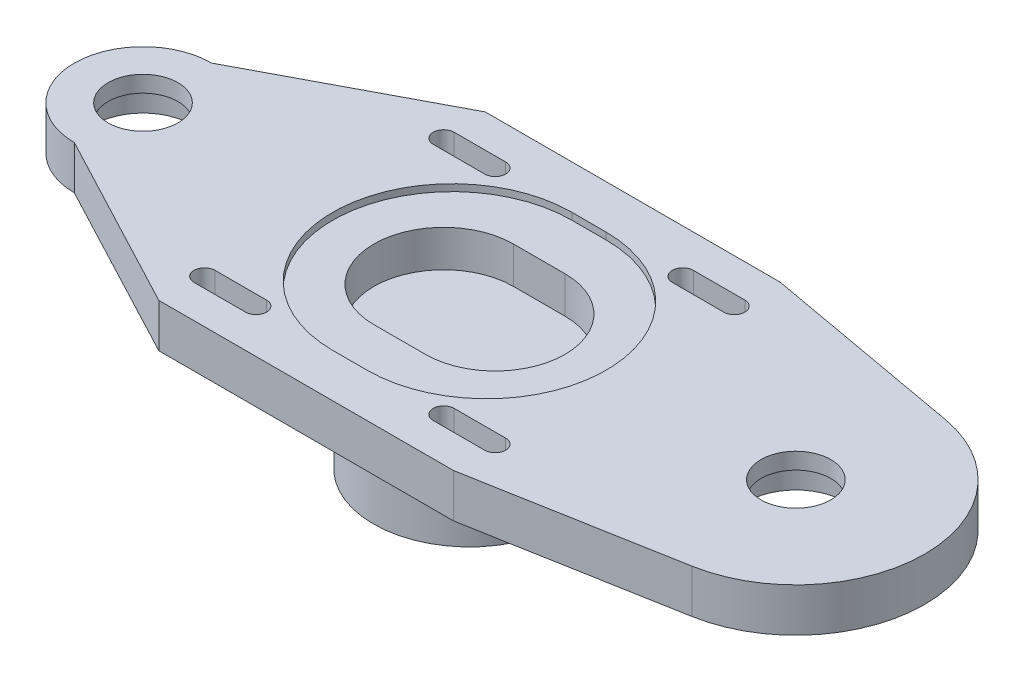
SolidWorks part; units mm, degrees
ref_plane "Front Plane" through (0, 0, 0) normal (0, 0, 1) x (1, 0, 0)
ref_plane "Top Plane" through (0, 0, 0) normal (0, 1, 0) x (1, 0, 0)
ref_plane "Right Plane" through (0, 0, 0) normal (1, 0, 0) x (0, 0, -1)
sketch "Sketch1" plane through (0, 0, 0) normal (0, 1, 0) x (1, 0, 0)
  line L0 (-95, 0) -> (0, 0) construction
  line L1 (-34.8, 34.8) -> (34.8, 34.8) construction
  line L2 (-34.8, 34.8) -> (-34.8, -34.8) construction
  line L3 (-34.8, -34.8) -> (34.8, -34.8) construction
  line L4 (34.8, 34.8) -> (34.8, -34.8) construction
  line L5 (-34.8, 34.8) -> (34.8, -34.8) construction
  line L6 (-34.8, -34.8) -> (34.8, 34.8) construction
  line L7 (-42.9, 47.5) -> (42.9, 47.5)
  line L8 (-42.9, 47.5) -> (-42.9, -47.5) construction
  line L9 (-42.9, -47.5) -> (42.9, -47.5)
  line L10 (42.9, 47.5) -> (42.9, -47.5) construction
  line L11 (-42.9, 47.5) -> (42.9, -47.5) construction
  line L12 (-42.9, -47.5) -> (42.9, 47.5) construction
  line L13 (0, 0) -> (95, 0) construction
  line L14 (-42.3, 34.8) -> (-27.3, 34.8) construction
  line L15 (-42.3, 37.85) -> (-27.3, 37.85)
  line L16 (-42.3, 31.75) -> (-27.3, 31.75)
  line L17 (42.3, 34.8) -> (27.3, 34.8) construction
  line L18 (42.3, 31.75) -> (27.3, 31.75)
  line L19 (42.3, 37.85) -> (27.3, 37.85)
  line L20 (42.3, -34.8) -> (27.3, -34.8) construction
  line L21 (42.3, -37.85) -> (27.3, -37.85)
  line L22 (42.3, -31.75) -> (27.3, -31.75)
  line L23 (-42.3, -34.8) -> (-27.3, -34.8) construction
  line L24 (-42.3, -31.75) -> (-27.3, -31.75)
  line L25 (-42.3, -37.85) -> (-27.3, -37.85)
  line L26 (-8, 0) -> (8, 0) construction
  line L27 (-8, 7.5) -> (8, 7.5)
  line L28 (-8, -7.5) -> (8, -7.5)
  line L29 (-42.9, 47.5) -> (-95, 20)
  line L31 (-95, -20) -> (-42.9, -47.5)
  line L32 (42.9, 47.5) -> (101.655, 36.9048)
  line L34 (101.655, -36.9048) -> (42.9, -47.5)
  circle A0 centre (-34.8, 34.8) radius 3.3 construction
  circle A1 centre (34.8, 34.8) radius 3.3 construction
  circle A2 centre (34.8, -34.8) radius 3.3 construction
  circle A3 centre (-34.8, -34.8) radius 3.3 construction
  circle A5 centre (-95, 0) radius 10.16
  circle A6 centre (-95, 0) radius 14.2875 construction
  arc A9 (-42.3, 37.85) -> (-42.3, 31.75) centre (-42.3, 34.8) ccw
  arc A10 (-27.3, 31.75) -> (-27.3, 37.85) centre (-27.3, 34.8) ccw
  arc A11 (42.3, 31.75) -> (42.3, 37.85) centre (42.3, 34.8) ccw
  arc A12 (27.3, 37.85) -> (27.3, 31.75) centre (27.3, 34.8) ccw
  arc A13 (42.3, -37.85) -> (42.3, -31.75) centre (42.3, -34.8) ccw
  arc A14 (27.3, -31.75) -> (27.3, -37.85) centre (27.3, -34.8) ccw
  arc A15 (-42.3, -31.75) -> (-42.3, -37.85) centre (-42.3, -34.8) ccw
  arc A16 (-27.3, -37.85) -> (-27.3, -31.75) centre (-27.3, -34.8) ccw
  arc A18 (-8, 7.5) -> (-8, -7.5) centre (-8, 0) ccw
  arc A19 (8, -7.5) -> (8, 7.5) centre (8, 0) ccw
  circle A20 centre (95, 0) radius 10.16
  circle A21 centre (95, 0) radius 14.2875 construction
  arc A22 (-95, 20) -> (-95, -20) centre (-95, 0) ccw
  circle A24 centre (95, 0) radius 29.21 construction
  arc A25 (101.655, -36.9048) -> (101.655, 36.9048) centre (95, 0) ccw
  point P0 (0, 0)
  point P18 (-34.8, 34.8)
  point P28 (34.8, 34.8)
  point P36 (34.8, -34.8)
  point P42 (-34.8, -34.8)
  point P49 (0, 0)
  dimension "D2" = 6.6
  dimension "D3" = 15
  dimension "D6" = 20.32
  dimension "D7" = 28.575
  dimension "D8" = 6.1
  dimension "D9" = 15
  dimension "D10" = 16
  dimension "D11" = 190
  dimension "D12" = 20
  dimension "D13" = 75
  dimension "D14" = 58.42
  dimension "D1" = 69.6
  dimension "D4" = 85.8
  dimension "D5" = 95
extrude "Boss-Extrude1" add sketch "Sketch1" along normal blind 12.7
sketch "Sketch2" plane through (0, 0, 0) normal (0, 1, 0) x (1, 0, 0)
  circle A0 centre (-95, 0) radius 14.2875
  circle A1 centre (95, 0) radius 14.2875
  dimension "D1" = 28.575
extrude "Cut-Extrude1" cut sketch "Sketch2" along normal blind 7.9375
sketch "Sketch3" plane through (0, 0, 0) normal (0, 1, 0) x (1, 0, 0)
  line L0 (-40.8, 34.8) -> (-28.8, 34.8) construction
  line L1 (-34.8, 34.8) -> (34.8, 34.8) construction
  line L2 (-34.8, 34.8) -> (-34.8, -34.8) construction
  line L3 (-34.8, -34.8) -> (34.8, -34.8) construction
  line L4 (34.8, 34.8) -> (34.8, -34.8) construction
  line L5 (-34.8, 34.8) -> (34.8, -34.8) construction
  line L6 (-34.8, -34.8) -> (34.8, 34.8) construction
  line L7 (-40.8, 40.05) -> (-28.8, 40.05)
  line L8 (-40.8, 29.55) -> (-28.8, 29.55)
  line L9 (40.8, 34.8) -> (28.8, 34.8) construction
  line L10 (40.8, 29.55) -> (28.8, 29.55)
  line L11 (40.8, 40.05) -> (28.8, 40.05)
  line L12 (40.8, -34.8) -> (28.8, -34.8) construction
  line L13 (40.8, -40.05) -> (28.8, -40.05)
  line L14 (40.8, -29.55) -> (28.8, -29.55)
  line L15 (-40.8, -34.8) -> (-28.8, -34.8) construction
  line L16 (-40.8, -29.55) -> (-28.8, -29.55)
  line L17 (-40.8, -40.05) -> (-28.8, -40.05)
  line L19 (-35.0265, 34.8) -> (-37.9132, 39.8) construction
  line L20 (-37.9132, 39.8) -> (-43.6868, 39.8) construction
  line L21 (-43.6868, 39.8) -> (-46.5735, 34.8) construction
  line L22 (-46.5735, 34.8) -> (-43.6868, 29.8) construction
  line L23 (-43.6868, 29.8) -> (-37.9132, 29.8) construction
  line L24 (-37.9132, 29.8) -> (-35.0265, 34.8) construction
  arc A0 (-40.8, 40.05) -> (-40.8, 29.55) centre (-40.8, 34.8) ccw
  arc A1 (-28.8, 29.55) -> (-28.8, 40.05) centre (-28.8, 34.8) ccw
  arc A2 (40.8, 29.55) -> (40.8, 40.05) centre (40.8, 34.8) ccw
  arc A3 (28.8, 40.05) -> (28.8, 29.55) centre (28.8, 34.8) ccw
  arc A4 (40.8, -40.05) -> (40.8, -29.55) centre (40.8, -34.8) ccw
  arc A5 (28.8, -29.55) -> (28.8, -40.05) centre (28.8, -34.8) ccw
  arc A6 (-40.8, -29.55) -> (-40.8, -40.05) centre (-40.8, -34.8) ccw
  arc A7 (-28.8, -40.05) -> (-28.8, -29.55) centre (-28.8, -34.8) ccw
  circle A8 centre (-40.8, 34.8) radius 5 construction
  point P0 (0, 0)
  point P8 (-34.8, 34.8)
  point P14 (34.8, 34.8)
  point P22 (34.8, -34.8)
  point P28 (-34.8, -34.8)
  dimension "D3" = 10
  dimension "D1" = 10.5
  dimension "D2" = 12
  dimension "D4" = 69.6
extrude "Cut-Extrude2" cut sketch "Sketch3" along normal blind 5 contours L17 A7 L16 A6 | L14 A5 L13 A4 | L11 A3 L10 A2 | A1 L7 A0 L8
sketch "Sketch4" plane through (0, 0, 0) normal (0, 1, 0) x (1, 0, 0)
  line L0 (-5, 0) -> (5, 0) construction
  line L1 (-5, 34.8) -> (5, 34.8)
  line L2 (-5, -34.8) -> (5, -34.8)
  arc A0 (-5, 34.8) -> (-5, -34.8) centre (-5, 0) ccw
  arc A1 (5, -34.8) -> (5, 34.8) centre (5, 0) ccw
  point P2 (0, 0)
  dimension "D1" = 10
  dimension "D2" = 69.6
extrude "Cut-Extrude3" cut sketch "Sketch4" against normal blind 2 from surface at 12.7 starting at face at (-95, 12.7, 10.16)
sketch "Sketch5" plane through (0, 0, 0) normal (0, 1, 0) x (1, 0, 0)
  line L0 (-7.5, 0) -> (7.5, 0) construction
  line L1 (-7.5, 20.32) -> (7.5, 20.32)
  line L2 (-7.5, -20.32) -> (7.5, -20.32)
  circle A0 centre (0, 0) radius 20.32 construction
  arc A1 (-7.5, 20.32) -> (-7.5, -20.32) centre (-7.5, 0) ccw
  arc A2 (7.5, -20.32) -> (7.5, 20.32) centre (7.5, 0) ccw
  point P5 (0, 0)
  dimension "D1" = 40.64
  dimension "D2" = 15
  dimension "D3" = 40.64
extrude "Cut-Extrude4" cut sketch "Sketch5" against normal blind 12 and the other way blind 22
sketch "Sketch6" plane through (0, 0, 0) normal (0, 1, 0) x (1, 0, 0)
  circle A0 centre (0, 0) radius 27.94
  dimension "D1" = 55.88
extrude "Boss-Extrude2" add sketch "Sketch6" against normal blind 32
